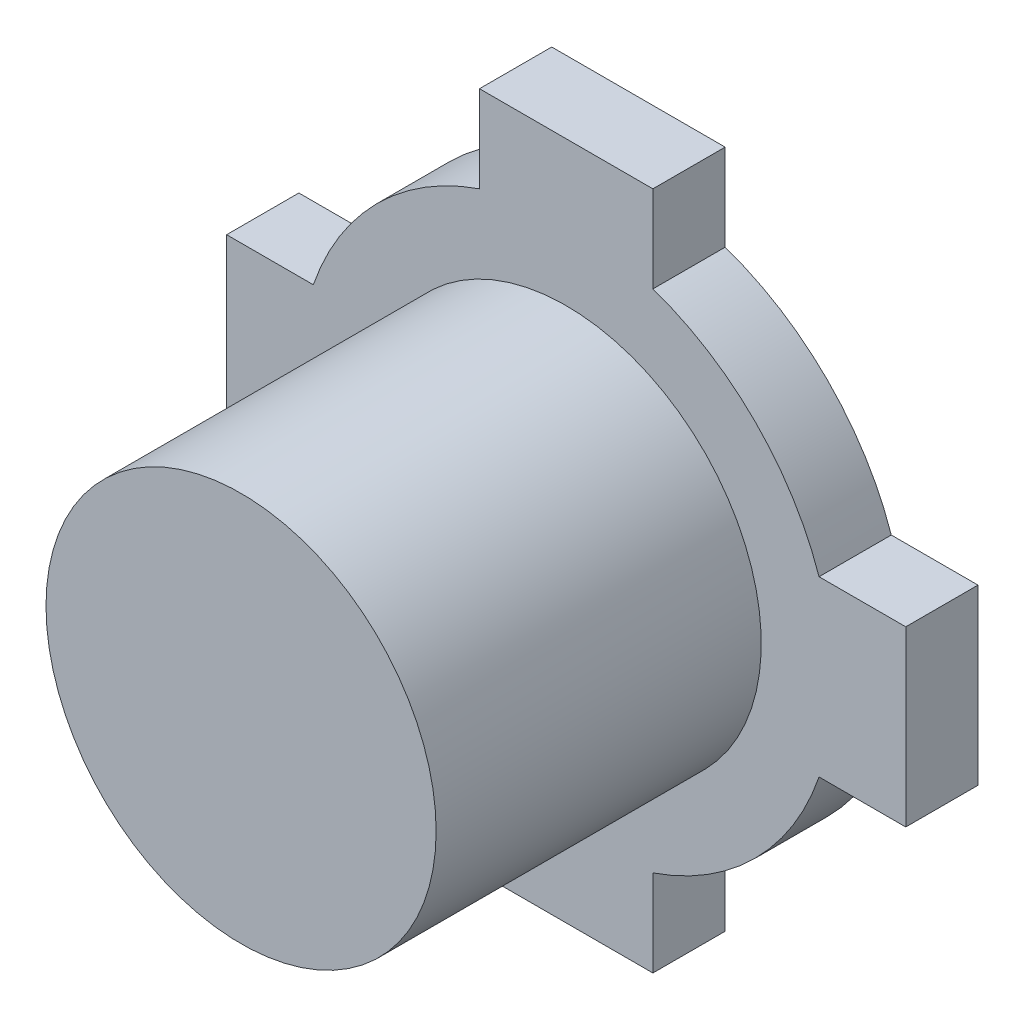
SolidWorks part; units mm, degrees
ref_plane "Front Plane" through (0, 0, 0) normal (0, 0, 1) x (1, 0, 0)
ref_plane "Top Plane" through (0, 0, 0) normal (0, 1, 0) x (1, 0, 0)
ref_plane "Right Plane" through (0, 0, 0) normal (1, 0, 0) x (0, 0, -1)
sketch "Sketch1" plane through (0, 0, 0) normal (0, 0, 1) x (1, 0, 0)
  circle A0 centre (0, 0) radius 2.7
  circle A1 centre (0, 0) radius 3 construction
  dimension "D1" = 0.3
extrude "Boss-Extrude1" add sketch "Sketch1" along normal blind 4.5
sketch "Sketch2" plane through (0, 0, 0) normal (0, 0, -1) x (-1, 0, 0)
  line L129 (-3.5, 1.2) -> (-4.7, 1.2)
  line L130 (-4.7, 1.2) -> (-4.7, -1.2)
  line L131 (-4.7, -1.2) -> (-3.5, -1.2)
  line L132 (-1.2, -3.5) -> (-1.2, -4.7)
  line L133 (-1.2, -4.7) -> (1.2, -4.7)
  line L134 (1.2, -4.7) -> (1.2, -3.5)
  line L135 (3.5, -1.2) -> (4.7, -1.2)
  line L136 (4.7, -1.2) -> (4.7, 1.2)
  line L137 (4.7, 1.2) -> (3.5, 1.2)
  line L138 (1.2, 3.5) -> (1.2, 4.7)
  line L139 (1.2, 4.7) -> (-1.2, 4.7)
  line L140 (-1.2, 4.7) -> (-1.2, 3.5)
  line L141 (-3.5, 1.2) -> (-4.7, 1.2)
  line L142 (-4.7, 1.2) -> (-4.7, -1.2)
  line L143 (-4.7, -1.2) -> (-3.5, -1.2)
  line L144 (-1.2, -3.5) -> (-1.2, -4.7)
  line L145 (-1.2, -4.7) -> (1.2, -4.7)
  line L146 (1.2, -4.7) -> (1.2, -3.5)
  line L147 (3.5, -1.2) -> (4.7, -1.2)
  line L148 (4.7, -1.2) -> (4.7, 1.2)
  line L149 (4.7, 1.2) -> (3.5, 1.2)
  line L150 (1.2, 3.5) -> (1.2, 4.7)
  line L151 (1.2, 4.7) -> (-1.2, 4.7)
  line L152 (-1.2, 4.7) -> (-1.2, 3.5)
  arc A35 (-1.2, 3.5) -> (-3.5, 1.2) centre (0, 0) ccw
  arc A36 (-3.5, -1.2) -> (-1.2, -3.5) centre (0, 0) ccw
  arc A37 (1.2, -3.5) -> (3.5, -1.2) centre (0, 0) ccw
  arc A38 (3.5, 1.2) -> (1.2, 3.5) centre (0, 0) ccw
  arc A39 (-1.2, 3.5) -> (-3.5, 1.2) centre (0, 0) ccw
  arc A40 (-3.5, -1.2) -> (-1.2, -3.5) centre (0, 0) ccw
  arc A41 (1.2, -3.5) -> (3.5, -1.2) centre (0, 0) ccw
  arc A42 (3.5, 1.2) -> (1.2, 3.5) centre (0, 0) ccw
  dimension "D1" = 0.3
extrude "Boss-Extrude2" add sketch "Sketch2" along normal blind 1
